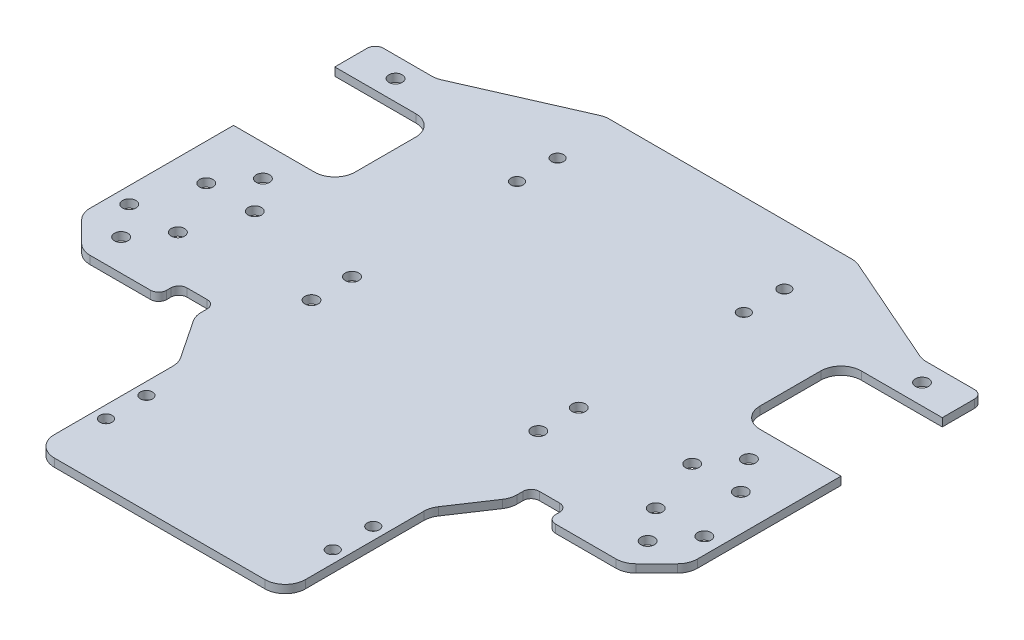
SolidWorks part; units mm, degrees
ref_plane "前视基准面" through (0, 0, 0) normal (0, 0, 1) x (1, 0, 0)
ref_plane "上视基准面" through (0, 0, 0) normal (0, 1, 0) x (1, 0, 0)
ref_plane "右视基准面" through (0, 0, 0) normal (1, 0, 0) x (0, 0, -1)
sketch "草图1" plane through (0, 0, 0) normal (0, 1, 0) x (1, 0, 0)
  line L1 (-75, -70.5) -> (75, -70.5)
  line L2 (-75, -70.5) -> (-75, 70.5)
  line L3 (-75, 70.5) -> (75, 70.5)
  line L4 (75, -70.5) -> (75, 70.5)
  line L5 (-75, -70.5) -> (75, 70.5) construction
  line L6 (-75, 70.5) -> (75, -70.5) construction
  point P0 (0, 0)
  dimension "D1" = 141
  dimension "D2" = 150
extrude "凸台-拉伸1" add sketch "草图1" along normal blind 2
sketch "草图2" plane through (0, 2, 0) normal (0, 1, 0) x (1, 0, 0)
  line L0 (-60, -11) -> (-65, -11) construction
  line L1 (-60, -11) -> (60, -11) construction
  line L2 (-60, -11) -> (-60, 11) construction
  line L3 (-60, 11) -> (60, 11) construction
  line L4 (60, -11) -> (60, 11) construction
  line L5 (-60, -11) -> (60, 11) construction
  line L6 (-60, 11) -> (60, -11) construction
  line L11 (-75, 70.5) -> (-75, -70.5) construction
  line L12 (-66, 7) -> (-54, 7) construction
  line L13 (-71, -15) -> (-59, -15) construction
  line L14 (-66, 7) -> (-66, 15) construction
  line L15 (-66, 15) -> (-54, 15) construction
  line L16 (-54, 7) -> (-54, 15) construction
  line L17 (-66, 7) -> (-54, 15) construction
  line L18 (-66, 15) -> (-54, 7) construction
  line L19 (-71, -15) -> (-71, -7) construction
  line L20 (-71, -7) -> (-59, -7) construction
  line L21 (-59, -15) -> (-59, -7) construction
  line L22 (-71, -15) -> (-59, -7) construction
  line L23 (-71, -7) -> (-59, -15) construction
  circle A4 centre (-60, 15) radius 1.65
  circle A5 centre (-66, 7) radius 1.65
  circle A6 centre (-54, 7) radius 1.65
  circle A7 centre (-71, -7) radius 1.65
  circle A8 centre (-59, -7) radius 1.65
  circle A9 centre (-65, -15) radius 1.65
  point P0 (0, 0)
  point P14 (-60, 0)
  dimension "D5" = 3.3
  dimension "D1" = 12
  dimension "D2" = 8
  dimension "D3" = 15
  dimension "D4" = 15
  dimension "D6" = 5
  dimension "D7" = 8
  dimension "D8" = 12
extrude "切除-拉伸1" cut sketch "草图2" against normal up to next
sketch "草图9" plane through (0, 2, 0) normal (0, 1, 0) x (1, 0, 0)
  line L0 (0, 22.75) -> (0, -22.75) construction
  line L1 (-75, -70.5) -> (-31, -70.5)
  line L2 (-75, -70.5) -> (-75, -22.75)
  line L3 (-75, -22.75) -> (-31, -22.75)
  line L4 (-31, -70.5) -> (-31, -22.75)
  line L5 (75, -70.5) -> (31, -70.5)
  line L6 (75, -70.5) -> (75, -22.75)
  line L7 (75, -22.75) -> (31, -22.75)
  line L8 (31, -70.5) -> (31, -22.75)
  point P14 (0, 0)
  dimension "D1" = 45.5
  dimension "D2" = 62
extrude "切除-拉伸5" cut sketch "草图9" against normal up to next
sketch "草图4" plane through (0, 2, 0) normal (0, 1, 0) x (1, 0, 0)
  line L1 (-31, -22.75) -> (-75, -22.75) construction
  line L2 (-75, 70.5) -> (-75, -22.75) construction
  line L3 (-39, -22.75) -> (-48, -22.75)
  line L4 (-39, -22.75) -> (-39, -17.75)
  line L5 (-39, -17.75) -> (-48, -17.75)
  line L6 (-48, -22.75) -> (-48, -17.75)
  dimension "D1" = 27
  dimension "D2" = 9
  dimension "D3" = 5
extrude "切除-拉伸2" cut sketch "草图4" against normal up to next
sketch "草图10" plane through (0, 2, 0) normal (0, 1, 0) x (1, 0, 0)
  line L0 (-75, 70.5) -> (-31, 70.5)
  line L1 (75, 70.5) -> (-75, 70.5) construction
  line L2 (-31, 70.5) -> (-60, 57.75)
  line L3 (-60, 57.75) -> (-75, 57.75)
  line L4 (-75, 70.5) -> (-75, -22.75) construction
  line L5 (-75, 57.75) -> (-75, 70.5)
  line L6 (-31, -70.5) -> (-31, 70.5) construction
  dimension "D1" = 15
  dimension "D2" = 12.75
extrude "切除-拉伸6" cut sketch "草图10" against normal up to next
mirror "镜向1" about plane through (0, 0, 0) normal (1, 0, 0) of "切除-拉伸6", "切除-拉伸1", "切除-拉伸2"
chamfer "倒角1" distance 8 angle 45 2 edges at (75, 1, 22.75) (-75, 1, 22.75)
sketch "草图5" plane through (0, 2, 0) normal (0, 1, 0) x (1, 0, 0)
  line L1 (-28, 5) -> (28, 5) construction
  line L2 (-28, 5) -> (-28, -5) construction
  line L3 (-28, -5) -> (28, -5) construction
  line L4 (28, 5) -> (28, -5) construction
  line L5 (-28, 5) -> (28, -5) construction
  line L6 (-28, -5) -> (28, 5) construction
  circle A0 centre (-28, 5) radius 1.65
  circle A1 centre (-28, -5) radius 1.65
  circle A2 centre (28, -5) radius 1.65
  circle A3 centre (28, 5) radius 1.65
  point P0 (0, 0)
  dimension "D3" = 3.3
  dimension "D1" = 56
  dimension "D2" = 10
extrude "切除-拉伸3" cut sketch "草图5" against normal up to next
sketch "草图7" plane through (0, 0, 0) normal (0, 1, 0) x (1, 0, 0)
  line L7 (-39, -22.75) -> (-31, -34.75)
  line L11 (-31, -70.5) -> (-31, -22.75) construction
  line L14 (-31, -34.75) -> (-31, -22.75)
  line L15 (-31, -22.75) -> (-39, -22.75)
  line L17 (31, -22.75) -> (39, -22.75)
  line L18 (39, -22.75) -> (31, -34.75)
  line L20 (31, -22.75) -> (31, -70.5) construction
  line L21 (31, -34.75) -> (31, -22.75)
  line L22 (-31, -34.75) -> (31, -34.75) construction
  dimension "D1" = 12
extrude "凸台-拉伸4" add sketch "草图7" along normal up to surface (2 mm away) up to face at (28, 2, -3.35)
sketch "草图8" plane through (0, 2, 0) normal (0, 1, 0) x (1, 0, 0)
  line L0 (0, 0) -> (0, -50.75) construction
  line L3 (-28, -55.75) -> (28, -55.75) construction
  line L4 (-28, -55.75) -> (-28, -45.75) construction
  line L5 (-28, -45.75) -> (28, -45.75) construction
  line L6 (28, -55.75) -> (28, -45.75) construction
  line L7 (-28, -55.75) -> (28, -45.75) construction
  line L8 (-28, -45.75) -> (28, -55.75) construction
  circle A0 centre (-28, -45.75) radius 1.5
  circle A1 centre (-28, -55.75) radius 1.5
  circle A2 centre (28, -45.75) radius 1.5
  circle A3 centre (28, -55.75) radius 1.5
  dimension "D4" = 3
  dimension "D1" = 10
  dimension "D2" = 56
  dimension "D3" = 50.75
extrude "切除-拉伸4" cut sketch "草图8" against normal up to next
sketch "草图11" plane through (0, 2, 0) normal (0, 1, 0) x (1, 0, 0)
  line L0 (-75, 57.75) -> (-75, -14.75) construction
  line L1 (-75, 47.75) -> (-50, 47.75)
  line L2 (-75, 47.75) -> (-75, 22.75)
  line L3 (-75, 22.75) -> (-50, 22.75)
  line L4 (-50, 47.75) -> (-50, 22.75)
  line L5 (-75, 57.75) -> (-60, 57.75) construction
  line L6 (0, 0) -> (0, 70.5) construction
  line L7 (31, 70.5) -> (-31, 70.5) construction
  line L8 (75, 22.75) -> (50, 22.75)
  line L9 (50, 47.75) -> (50, 22.75)
  line L10 (75, 47.75) -> (50, 47.75)
  line L11 (75, 47.75) -> (75, 22.75)
  dimension "D1" = 10
  dimension "D2" = 25
  dimension "D3" = 25
extrude "切除-拉伸7" cut sketch "草图11" against normal up to next
mirror "镜向2" about plane through (0, 0, 0) normal (0, 0, 1) of "切除-拉伸4"
fillet "圆角5" radius 5 18 edges at (75, 1, 14.75) (67, 1, 22.75) (-67, 1, 22.75) (-75, 1, 14.75) (50, 1, -22.75) (50, 1, -47.75) (-50, 1, -22.75) (-50, 1, -47.75) (31, 1, 34.75) (-31, 1, 34.75) (39, 1, 22.75) (-39, 1, 22.75) (60, 1, -57.75) (31, 1, -70.5) (-31, 1, -70.5) (-60, 1, -57.75) (31, 1, 70.5) (-31, 1, 70.5)
fillet "圆角6" radius 2 6 edges at (48, 1, 22.75) (48, 1, 17.75) (39, 1, 17.75) (-39, 1, 17.75) (-48, 1, 22.75) (-48, 1, 17.75)
sketch "草图12" plane through (0, 2, 0) normal (0, 1, 0) x (1, 0, 0)
  line L0 (-75, 52.75) -> (-65, 52.75) construction
  line L1 (-75, 57.75) -> (-75, 47.75) construction
  line L2 (0, 0) -> (0, 70.5) construction
  line L3 (29.9494, 70.5) -> (-29.9494, 70.5) construction
  circle A0 centre (-65, 52.75) radius 1.65
  circle A1 centre (65, 52.75) radius 1.65
  dimension "D1" = 3.3
  dimension "D2" = 10
extrude "切除-拉伸8" cut sketch "草图12" against normal up to next
fillet "圆角7" radius 2 2 edges at (75, 1, -57.75) (-75, 1, -57.75)
